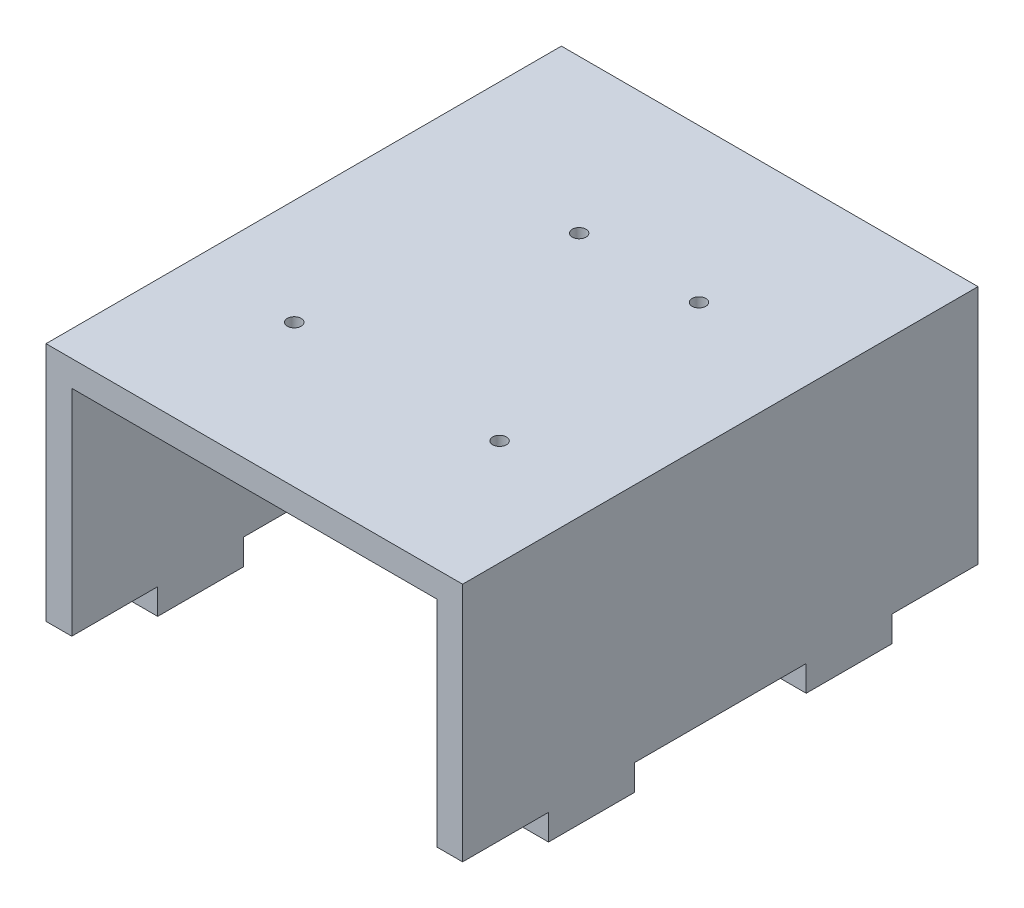
SolidWorks part; units mm, degrees
ref_plane "Front Plane" through (0, 0, 0) normal (0, 0, 1) x (1, 0, 0)
ref_plane "Top Plane" through (0, 0, 0) normal (0, 1, 0) x (1, 0, 0)
ref_plane "Right Plane" through (0, 0, 0) normal (1, 0, 0) x (0, 0, -1)
sketch "Sketch1" plane through (0, 0, 0) normal (0, 0, 1) x (1, 0, 0)
  line L0 (0, 0) -> (-42.5, 0) construction
  line L1 (0, 0) -> (42.5, 0) construction
  line L2 (42.5, 0) -> (42.5, 50)
  line L3 (42.5, 50) -> (-42.5, 50)
  line L4 (-42.5, 50) -> (-42.5, 0)
  line L5 (-42.5, 0) -> (-48.5, 0)
  line L6 (-48.5, 0) -> (-48.5, 56)
  line L7 (-48.5, 56) -> (48.5, 56)
  line L8 (48.5, 56) -> (48.5, 0)
  line L9 (48.5, 0) -> (42.5, 0)
  dimension "D1" = 42.5
  dimension "D2" = 42.5
  dimension "D3" = 50
  dimension "D4" = 6
  dimension "D5" = 6
  dimension "D6" = 6
extrude "Boss-Extrude1" add sketch "Sketch1" along normal blind 120
sketch "Sketch2" plane through (48.5, 0, 0) normal (1, 0, 0) x (0, 0, -1)
  line L0 (-60, 0) -> (-60, 56) construction
  line L1 (-120, 0) -> (0, 0) construction
  line L2 (-120, 56) -> (0, 56) construction
  line L4 (0, 0) -> (-20, 0)
  line L5 (-20, 0) -> (-20, -6)
  line L6 (-20, -6) -> (-40, -6)
  line L7 (-40, -6) -> (-40, 0)
  line L8 (-100, 0) -> (-100, -6)
  line L9 (-100, -6) -> (-80, -6)
  line L10 (-80, -6) -> (-80, 0)
  line L11 (-100, 0) -> (-80, 0)
  line L12 (-40, 0) -> (-20, 0)
  line M9 (-120, 0) -> (0, 0)
  dimension "D1" = 20
  dimension "D2" = 20
  dimension "D3" = 6
extrude "Boss-Extrude2" add sketch "Sketch2" against normal blind 6 contours L9 L10 L8 M9 | L7 L6 L5 M9
sketch "Sketch3" plane through (-48.5, 0, 0) normal (-1, 0, 0) x (0, 0, 1)
  line L0 (60, 0) -> (60, 56) construction
  line L1 (120, 0) -> (0, 0) construction
  line L2 (120, 56) -> (0, 56) construction
  line L3 (20, 0) -> (20, -6)
  line L4 (20, -6) -> (40, -6)
  line L5 (40, -6) -> (40, 0)
  line L6 (20, 0) -> (40, 0)
  line L7 (100, -6) -> (80, -6)
  line L8 (100, 0) -> (100, -6)
  line L9 (100, 0) -> (80, 0)
  line L10 (80, -6) -> (80, 0)
  dimension "D1" = 6
  dimension "D2" = 20
extrude "Boss-Extrude3" add sketch "Sketch3" against normal blind 6
sketch "Sketch4" plane through (0, 56, 0) normal (0, 1, 0) x (1, 0, 0)
  line L0 (0, -120) -> (0, 0) construction
  line L1 (48.5, -120) -> (-48.5, -120) construction
  line L2 (48.5, 0) -> (-48.5, 0) construction
  line L3 (-23.905, -86.7984) -> (23.905, -86.7984) construction
  line L4 (-8.71, -35.6584) -> (19.19, -35.6584) construction
  circle A0 centre (-23.905, -86.7984) radius 1.6
  circle A1 centre (23.905, -86.7984) radius 1.6
  circle A2 centre (-8.71, -35.6584) radius 1.6
  circle A3 centre (19.19, -35.6584) radius 1.6
  point P9 (0, -86.7984)
  point P14 (0, -35.6584)
  dimension "D1" = 3.2
  dimension "D5" = 27.9
  dimension "D2" = 47.81
  dimension "D3" = 23.905
  dimension "D4" = 8.71
  dimension "D6" = 51.14
extrude "Cut-Extrude1" cut sketch "Sketch4" against normal blind 10
